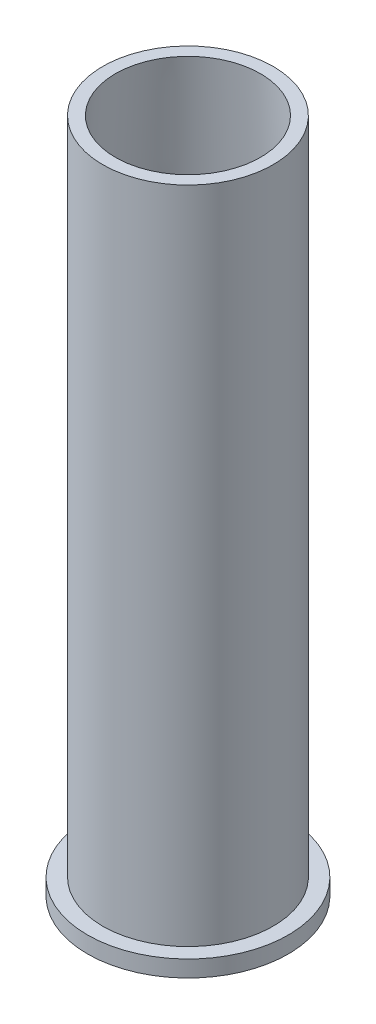
SolidWorks part; units mm, degrees
ref_plane "Alzado" through (0, 0, 0) normal (0, 0, 1) x (1, 0, 0)
ref_plane "Planta" through (0, 0, 0) normal (0, 1, 0) x (1, 0, 0)
ref_plane "Vista lateral" through (0, 0, 0) normal (1, 0, 0) x (0, 0, -1)
sketch "Croquis1" plane through (0, 0, 0) normal (0, 1, 0) x (1, 0, 0)
  circle A0 centre (0, 0) radius 18.2625
  dimension "D1" = 36.525
extrude "Saliente-Extruir1" add sketch "Croquis1" along normal blind 3
sketch "Croquis2" plane through (0, 3, 0) normal (0, 1, 0) x (1, 0, 0)
  circle A0 centre (0, 0) radius 15.5
  dimension "D1" = 31
extrude "Saliente-Extruir2" add sketch "Croquis2" along normal blind 120
sketch "Croquis3" plane through (0, 0, 0) normal (0, -1, 0) x (1, 0, 0)
  circle A0 centre (0, 0) radius 14.75
  dimension "D1" = 29.5
extrude "Cortar-Extruir1" cut sketch "Croquis3" against normal blind 102
sketch "Croquis4" plane through (0, 0, 0) normal (0, 0, 1) x (1, 0, 0)
  line L0 (0, 123) -> (0, 102) construction
  line L1 (15.5, 123) -> (-15.5, 123) construction
  line L2 (-14.75, 102) -> (14.75, 102) construction
  line L3 (0, 102) -> (-14.75, 102)
  line L4 (-14.75, 102) -> (-13.2, 123)
  line L5 (-13.2, 123) -> (0, 123)
  line L6 (0, 123) -> (0, 102)
  dimension "D1" = 13.2
  dimension "D2" = 14.75
revolve "Cortar-Revolución3" cut sketch "Croquis4" angle 360 about L0
